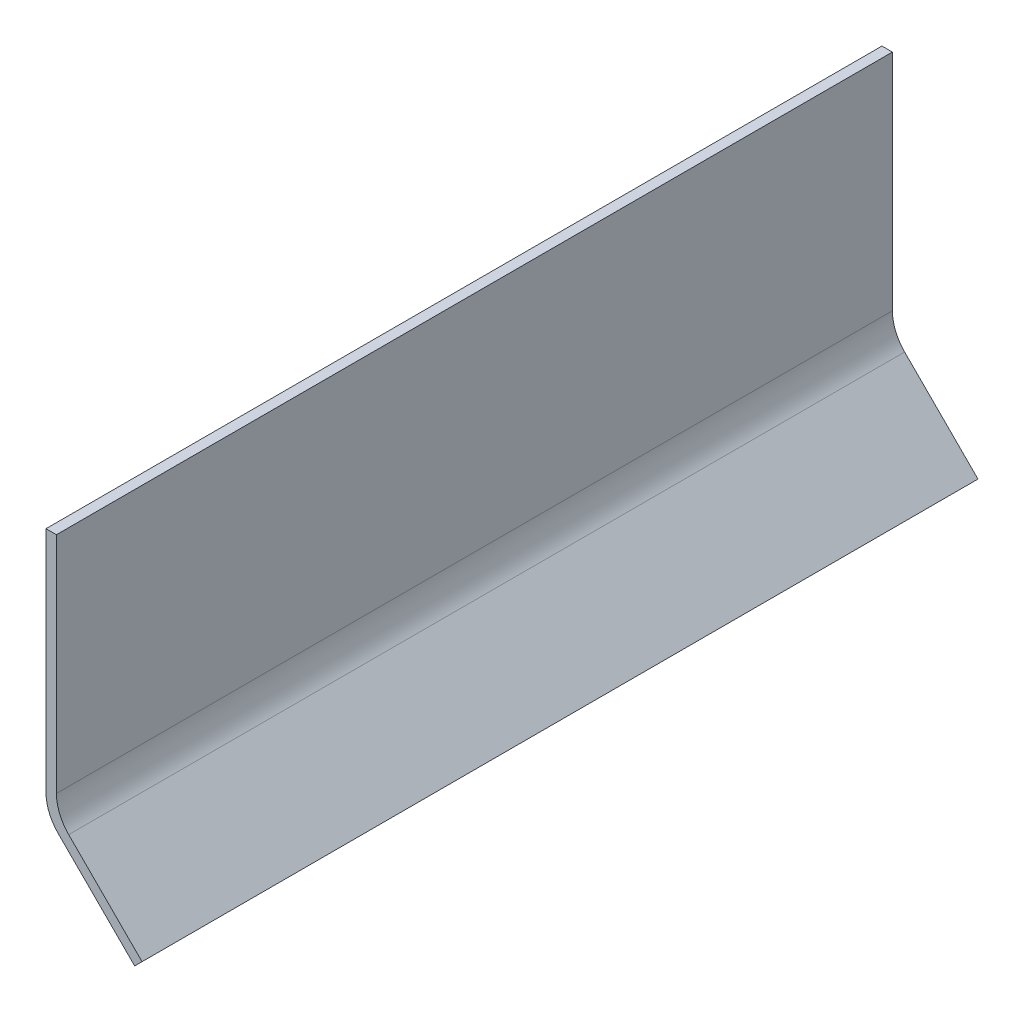
SolidWorks part; units mm, degrees
material "Acrylic (Medium-high impact)"
ref_plane "Front Plane" through (0, 0, 0) normal (0, 0, 1) x (1, 0, 0)
ref_plane "Top Plane" through (0, 0, 0) normal (0, 1, 0) x (1, 0, 0)
ref_plane "Right Plane" through (0, 0, 0) normal (1, 0, 0) x (0, 0, -1)
sketch "Sketch1" plane through (0, 0, 0) normal (0, 0, 1) x (1, 0, 0)
  line L0 (0, 16.1006) -> (0, 50.8)
  line L1 (1.8599, 11.6105) -> (13.4704, 0)
  line L2 (0, 0) -> (13.4704, 0) construction
  line L3 (0, 50.8) -> (1.5875, 50.8)
  line L4 (1.5875, 50.8) -> (1.5875, 16.7582)
  line L5 (3.4474, 12.2681) -> (14.5929, 1.1225)
  line L6 (14.5929, 1.1225) -> (13.4704, 0)
  arc A0 (1.5875, 16.7582) -> (3.4474, 12.2681) centre (7.9375, 16.7582) ccw
  arc A1 (1.8599, 11.6105) -> (0, 16.1006) centre (6.35, 16.1006) cw
  point P12 (0, 13.4704)
  dimension "D6" = 6.35
  dimension "D1" = 45
  dimension "D2" = 19.05
  dimension "D3" = 50.8
  dimension "D4" = 1.5875
  dimension "D5" = 1.5875
extrude "Boss-Extrude1" add sketch "Sketch1" along normal mid plane 127
